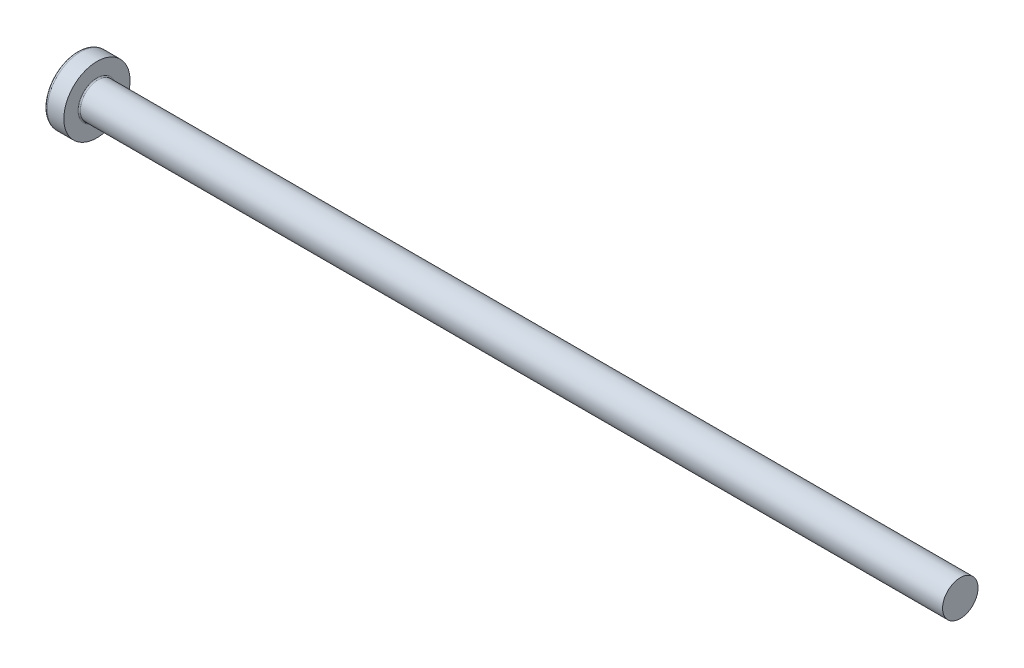
SolidWorks part; units mm, degrees
ref_plane "Plane1" through (0, 0, 0) normal (0, 0, 1) x (1, 0, 0)
ref_plane "Plane2" through (0, 0, 0) normal (0, 1, 0) x (1, 0, 0)
ref_plane "Plane3" through (0, 0, 0) normal (1, 0, 0) x (0, 0, -1)
sketch "BodySke" plane through (0, 0, 0) normal (0, 0, 1) x (1, 0, 0)
  line L0 (2.4, 1.5) -> (2.4, 2.8)
  line L1 (2.65, 6.35) -> (2.65, -3.175) construction
  line L2 (-25.4, 0) -> (127, 0) construction
  line L3 (75.4, 0) -> (0, 0)
  line L4 (2.4, 1.5) -> (75.4, 1.5)
  line L5 (75.4, 1.5) -> (75.4, 0)
  line L6 (1.0035, 2.8) -> (2.4, 2.8)
  line L8 (2.4, 6.35) -> (2.4, -3.175) construction
  arc A0 (0.7754, 2.6744) -> (0, 0) centre (5, 0) ccw
  arc A2 (0.7754, 2.6744) -> (1.0035, 2.8) centre (1.0035, 2.53) cw
  dimension "Head_crown_rad" = 5
  dimension "Head_fillet_rad" = 0.27
  dimension "Length" = 73
  dimension "Head_ht" = 2.4
  dimension "Head_dia" = 5.6
  dimension "Advance" = 0.5
  dimension "Thread_nom" = 73
  dimension "Diameter" = 3
revolve "Base-Revolve" add sketch "BodySke"
cosmetic thread "ThreadCosmetic" [suppressed]
fillet "Fillet1" radius 0.1 1 edges at (2.4, 0, 1.5)
sketch "Sketch3" plane through (0, 0, 0) normal (1, 0, 0) x (0, 0, -1)
  line L0 (0.37, -1.4) -> (-0.37, -1.4)
  line L1 (0.37, -1.4) -> (0.37, 1.4)
  line L2 (-0.37, 1.4) -> (0.37, 1.4)
  line L3 (-0.37, 1.4) -> (-0.37, -1.4)
  dimension "Cross_dia" = 2.8
  dimension "D1" = 1.4
  dimension "Cross_width" = 0.74
  dimension "D2" = 0.37
ref_plane "Plane4" through (1.75, 0, 0) normal (1, 0, 0) x (0, 0, -1)
sketch "Sketch4" plane through (1.75, 0, 0) normal (1, 0, 0) x (0, 0, -1)
  line L0 (0.37, -0.5275) -> (-0.37, -0.5275)
  line L1 (0.37, -0.5275) -> (0.37, 0.5275)
  line L2 (-0.37, 0.5275) -> (0.37, 0.5275)
  line L3 (-0.37, 0.5275) -> (-0.37, -0.5275)
  dimension "D1" = 0.74
  dimension "D2" = 1.055
  dimension "D3" = 0.37
  dimension "D4" = 0.5275
loft "Recess" cut profiles "Sketch3", "Sketch4"
pattern_circular "RecPat" count 2 every 90 about axis through (0, 0, 0) along (1, 0, 0) of "Recess"
sketch "RecCorSke" plane through (0, 0, 0) normal (0, 0, 1) x (1, 0, 0)
  line L0 (-3.175, 0) -> (15.875, 0) construction
  line L1 (-25.4, 0) -> (127, 0) construction
  line L2 (0, 0) -> (0, 0.6784)
  line L3 (0, 0.6784) -> (1.75, 0.556)
  line L4 (1.75, 0.556) -> (1.9307, 0)
  line L5 (1.9307, 0) -> (0, 0)
  dimension "Diameter" = 1.112
  dimension "Depth" = 1.75
  dimension "Draft_angle" = 4
  dimension "Bottom_angle" = 18
revolve "RecessCore" cut sketch "RecCorSke" angle 360 about L0
sketch "ThdSchSke" plane through (0, 0, 0) normal (0, 0, 1) x (1, 0, 0)
  line L0 (3.4, -1.2195) -> (3.2036, -1.5)
  line L1 (3.4, -1.2195) -> (3.5964, -1.5)
  line L2 (3.5964, -1.5) -> (3.5964, -1.875)
  line L3 (-3.175, 0) -> (5.1513, 0) construction
  line L5 (3.5964, -1.875) -> (3.2036, -1.875)
  line L6 (3.2036, -1.875) -> (3.2036, -1.5)
  dimension "Diameter" = 3
  dimension "SideAngle" = 55
  dimension "VeeAngle" = 70
  dimension "Thread_minor" = 2.439
  dimension "Overcut" = 3.75
  dimension "Start" = 3.4
revolve "ThreadSchematic" [suppressed] cut sketch "ThdSchSke" angle 360 about L3
pattern_linear "ThdSchPat" [suppressed]
equation "\"D1@Sketch3\" = \"Cross_dia@Sketch3\" / 2"
equation "\"D2@Sketch3\" = \"Cross_width@Sketch3\" / 2"
equation "\"Depth@RecCorSke\" = \"Cross_depth@Plane4\""
equation "\"D1@Sketch4\" = \"Cross_width@Sketch3\""
equation "\"D2@Sketch4\" = \"Cross_dia@Sketch3\" - 2.0 * \"Cross_depth@Plane4\" * tan(26.5  * 0.017453292)"
equation "\"D3@Sketch4\" = \"D1@Sketch4\" / 2"
equation "\"D4@Sketch4\" = \"D2@Sketch4\" / 2"
equation "\"Thread_length@ThreadCosmetic\" = ((sgn( (\"Length@BodySke\" - \"Advance@BodySke\" * 2.0 ) - \"Thread_nom@BodySke\" )-1)*( (\"Length@BodySke\" - \"Advance@BodySke\" * 2.0 ) - \"Thread_nom@BodySke\" ))/-2+ \"Thread_nom@BodySke\""
equation "\"Thread_minor@ThdSchSke\" = \"Thread_minor@ThreadCosmetic\""
equation "\"Diameter@ThdSchSke\" = \"Diameter@BodySke\""
equation "\"Overcut@ThdSchSke\" = \"Diameter@BodySke\" * 1.25"
equation "\"Start@ThdSchSke\" = \"Head_ht@BodySke\" + \"Length@BodySke\" - \"Thread_length@ThreadCosmetic\"  '---Non-countersunk---"
equation "\"Num_threads@ThdSchPat\" = int( \"Thread_length@ThreadCosmetic\" / \"Advance@BodySke\" + 0.999 )  + 1"
equation "\"Advance@ThdSchPat\" = \"Thread_length@ThreadCosmetic\" /  (\"Num_threads@ThdSchPat\" - 1) 'relax it"
